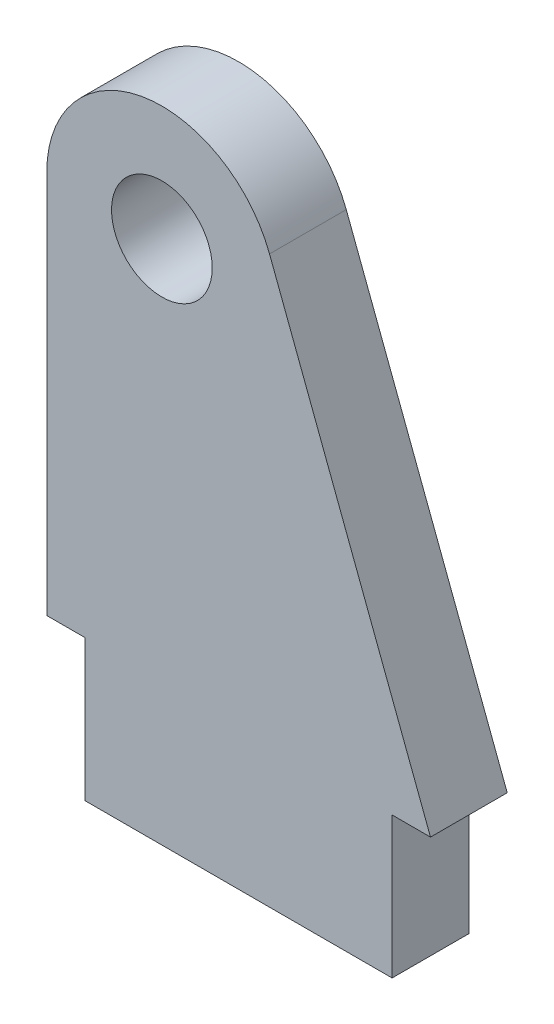
SolidWorks part; units mm, degrees
ref_plane "Front Plane" through (0, 0, 0) normal (0, 0, 1) x (1, 0, 0)
ref_plane "Top Plane" through (0, 0, 0) normal (0, 1, 0) x (1, 0, 0)
ref_plane "Right Plane" through (0, 0, 0) normal (1, 0, 0) x (0, 0, -1)
sketch "Sketch1" plane through (0, 0, 0) normal (0, 0, 1) x (1, 0, 0)
  line L0 (7.9375, 2.921) -> (1.2781, 20.4845)
  line L1 (6.35, -2.921) -> (-6.35, -2.921)
  line L2 (6.35, -2.921) -> (6.35, 2.921)
  line L3 (6.35, 2.921) -> (7.9375, 2.921)
  line L4 (-6.35, -2.921) -> (-6.35, 2.921)
  line L5 (6.35, -2.921) -> (-6.35, 2.921) construction
  line L6 (6.35, 2.921) -> (-6.35, -2.921) construction
  line L7 (-7.9375, 2.921) -> (-6.35, 2.921)
  line L8 (-7.9375, 2.921) -> (-7.9375, 18.796)
  circle A0 centre (-3.175, 18.796) radius 2.0828
  arc A1 (1.2781, 20.4845) -> (-7.9375, 18.796) centre (-3.175, 18.796) ccw
  point P0 (0, 0)
  dimension "D8" = 9.525
  dimension "D6" = 4.1656
  dimension "D1" = 12.7
  dimension "D2" = 5.842
  dimension "D3" = 15.875
  dimension "D4" = 1.5875
  dimension "D5" = 1.5875
  dimension "D7" = 3.175
extrude "Boss-Extrude1" add sketch "Sketch1" along normal blind 3.175
